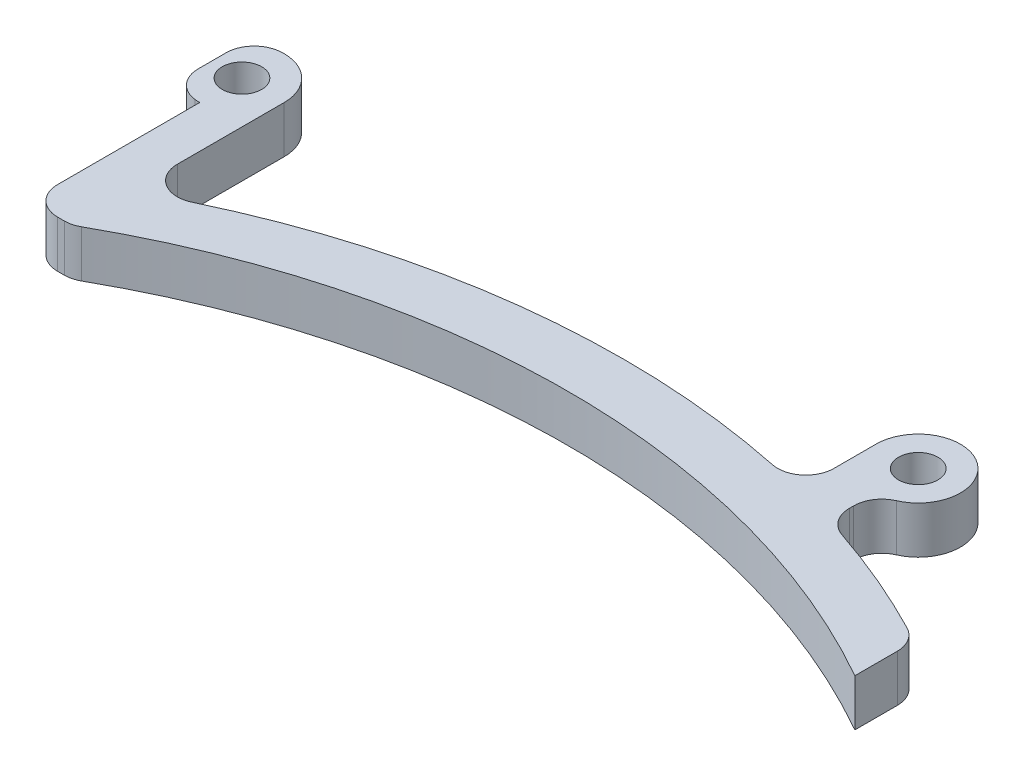
SolidWorks part; units mm, degrees
ref_plane "Front" through (0, 0, 0) normal (0, 0, 1) x (1, 0, 0)
ref_plane "Top" through (0, 0, 0) normal (0, 1, 0) x (1, 0, 0)
ref_plane "Right" through (0, 0, 0) normal (1, 0, 0) x (0, 0, -1)
sketch "Sketch1" plane through (0, 0, 0) normal (0, 1, 0) x (1, 0, 0)
  line L0 (72, -9.5031) -> (72, -4.5)
  line L1 (0, -22.6291) -> (0, -4.5)
  line L2 (4.5, 0) -> (4.5, -16.3012)
  line L4 (67.5, 0) -> (67.5, -8.2361)
  line L5 (87.7275, -16.1523) -> (87.7275, -22.4737)
  line L6 (0, -22.6291) -> (4.5, -22.6291)
  line L7 (-3.182, -3.182) -> (-3.182, 3.182)
  circle A0 centre (0, 0) radius 2.1
  circle A1 centre (72, 0) radius 2.1
  arc A2 (4.5, 0) -> (-3.182, 3.182) centre (0, 0) ccw
  arc A3 (72, -4.5) -> (67.5, 0) centre (72, 0) ccw
  arc A6 (4.5, -16.3012) -> (67.5, -8.2361) centre (46.25, -92.3358) cw
  arc A7 (4.5, -22.6291) -> (87.7275, -22.4737) centre (46.25, -95.5181) cw
  arc A8 (72, -9.5031) -> (87.7275, -16.1523) centre (46.25, -92.3358) cw
  arc A9 (-3.182, -3.182) -> (0, -4.5) centre (0, 0) ccw
extrude "Boss-Extrude1" add sketch "Sketch1" along normal blind 5
fillet "Fillet1" radius 3 9 edges at (67.5, 2.5, 8.2361) (72, 2.5, 4.5) (72, 2.5, 9.5031) (87.7275, 2.5, 16.1523) (0, 2.5, 22.6291) (4.5, 2.5, 16.3012) (4.5, 2.5, 22.6291) (-3.182, 2.5, -3.182) (-3.182, 2.5, 3.182)
